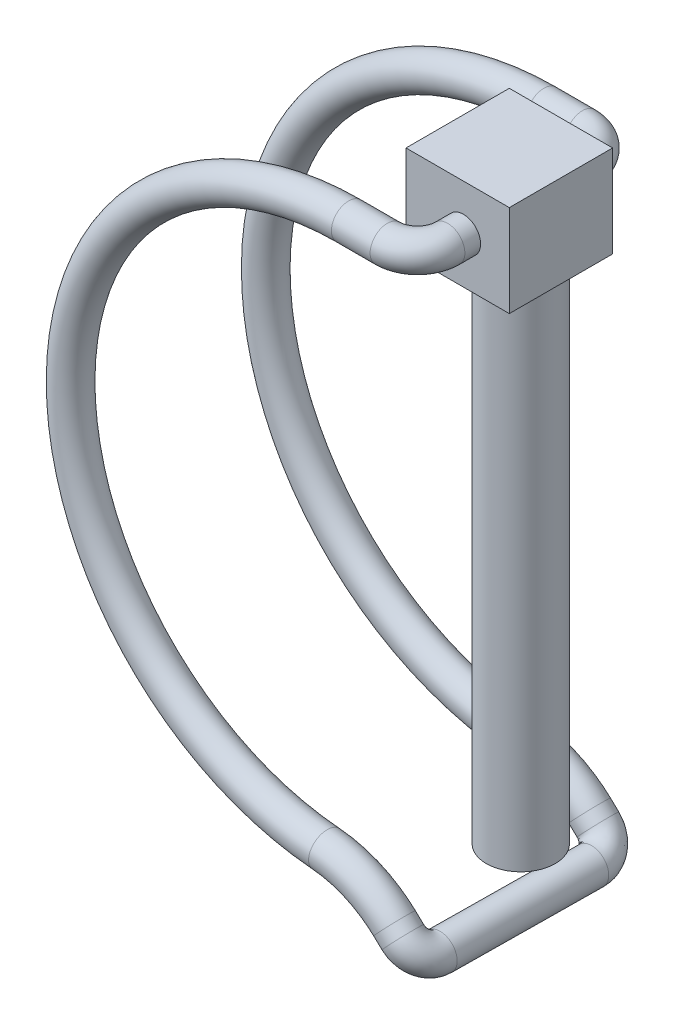
SolidWorks part; units mm, degrees
material "1.7016 (17Cr3)"
ref_plane "Płaszczyzna przednia" through (0, 0, 0) normal (0, 0, 1) x (1, 0, 0)
ref_plane "Płaszczyzna górna" through (0, 0, 0) normal (0, 1, 0) x (1, 0, 0)
ref_plane "Płaszczyzna prawa" through (0, 0, 0) normal (1, 0, 0) x (0, 0, -1)
sketch "Szkic1" plane through (0, 0, 0) normal (0, 1, 0) x (1, 0, 0)
  circle A0 centre (0, 0) radius 1.5
  dimension "D1" = 3
extrude "Dodanie-wyciągnięcie1" add sketch "Szkic1" along normal blind 22
sketch "Szkic2" plane through (0, 22, 0) normal (0, 1, 0) x (1, 0, 0)
  line L1 (-2.75, 2.25) -> (1.75, 2.25)
  line L2 (-2.75, 2.25) -> (-2.75, -2.25)
  line L3 (-2.75, -2.25) -> (1.75, -2.25)
  line L4 (1.75, 2.25) -> (1.75, -2.25)
  line L5 (-2.75, 2.25) -> (1.75, -2.25) construction
  line L6 (-2.75, -2.25) -> (1.75, 2.25) construction
  point P0 (-0.5, 0)
  dimension "D1" = 4.5
  dimension "D2" = 4.5
  dimension "D3" = 0.5
extrude "Dodanie-wyciągnięcie2" add sketch "Szkic2" along normal blind 4
sketch "Szkic3" plane through (0, 0, 2.25) normal (0, 0, 1) x (1, 0, 0)
  line L0 (-2.75, 26) -> (1.75, 26) construction
  line L1 (1.75, 26) -> (1.75, 22) construction
  circle A0 centre (-0.25, 24) radius 0.75
  dimension "D1" = 1.5
  dimension "D2" = 2
  dimension "D3" = 2
sketch3d "Szkic 3D1"
  line L0 (-0.25, 24, 2.25) -> (-0.25, 24, 2.9358)
  line L1 (-1.5642, 24, 4.25) -> (-3.25, 24, 4.25)
  arc A0 (-0.25, 24, 2.9358) -> (-1.5642, 24, 4.25) centre (-1.5642, 24, 2.9358) ccw
  arc A1 (-3.25, 24, 4.25) -> (-4.2431, -0.18, 4.25) centre (-3.25, 11.8896, 4.25) ccw
  arc A2 (-4.2431, -0.18, 4.25) -> (-1.25, -1.5, 4.25) centre (-4.6532, -5.1631, 4.25) ccw
  point P3 (-1.5642, 22.6858, 2.9358)
  point P7 (-3.25, 11.8896, 16.3604)
  point P17 (-4.6532, -5.1631, -0.75)
  dimension "D1" = 5
  dimension "D2" = 2
  dimension "D3" = 3
  dimension "D4" = 0.5
  dimension "D5" = 1.5
sweep "Wyciągnięcie po ścieżce1" add profiles "Szkic3" path "Szkic 3D1"
mirror "Lustro1" about plane through (0, 0, 0) normal (0, 0, 1) of "Wyciągnięcie po ścieżce1"
sketch "Szkic4" plane through (0.077, -0.0716, 0) normal (0.7326, -0.6806, 0) x (0, 0, -1)
  circle A0 centre (4.25, -1.9497) radius 0.75 construction
  circle A1 centre (-4.25, -1.9497) radius 0.75 construction
  circle A2 centre (-4.25, -1.9497) radius 0.75
  point P0 (-4.25, -1.9497)
  point P1 (4.25, -1.9497)
ref_plane "Płaszczyzna1" through (-1.327, -1.4284, 0) normal (0.6806, 0.7326, 0) x (0.7326, -0.6806, 0.0077)
sketch "Szkic5" plane through (-1.327, -1.4284, 0) normal (0.6806, 0.7326, 0) x (0.7326, -0.6806, 0.0077)
  line L0 (0.1378, -4.2491) -> (0.6378, -4.2491)
  line L1 (1.5726, -3.3143) -> (1.5726, 3.2507)
  line L2 (0.5726, 4.2507) -> (0.0726, 4.2507)
  arc A0 (0.6378, -4.2491) -> (1.5726, -3.3143) centre (0.6378, -3.3143) ccw
  arc A1 (1.5726, 3.2507) -> (0.5726, 4.2507) centre (0.5726, 3.2507) ccw
  dimension "D1" = 1.5
  dimension "D2" = 0.5
  dimension "D3" = 0.5
sweep "Wyciągnięcie po ścieżce3" add profiles "Szkic4" path "Szkic5"
